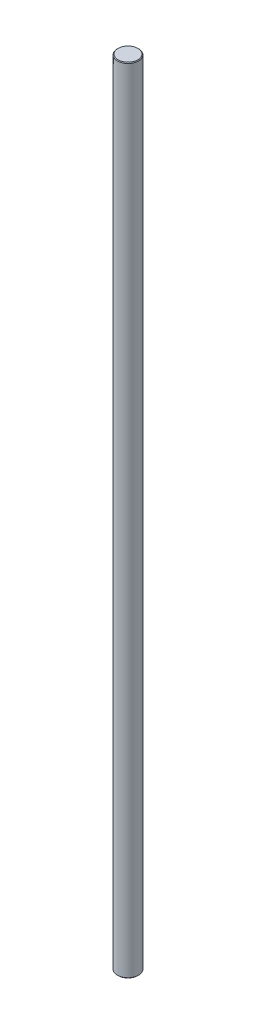
SolidWorks part; units mm, degrees
material "1.4571 (X6CrNiMoTi17-12-2)"
ref_plane "Płaszczyzna przednia" through (0, 0, 0) normal (0, 0, 1) x (1, 0, 0)
ref_plane "Płaszczyzna górna" through (0, 0, 0) normal (0, 1, 0) x (1, 0, 0)
ref_plane "Płaszczyzna prawa" through (0, 0, 0) normal (1, 0, 0) x (0, 0, -1)
sketch "Szkic1" plane through (0, 0, 0) normal (0, 1, 0) x (1, 0, 0)
  circle A0 centre (-19.4218, 6.0076) radius 4
extrude "Dodanie-wyciągnięcie1" add sketch "Szkic1" along normal blind 300
chamfer "Sfazowanie1" distance 0.25 angle 45 2 edges at (-19.4218, 300, -2.0076) (-19.4218, 0, -2.0076)
